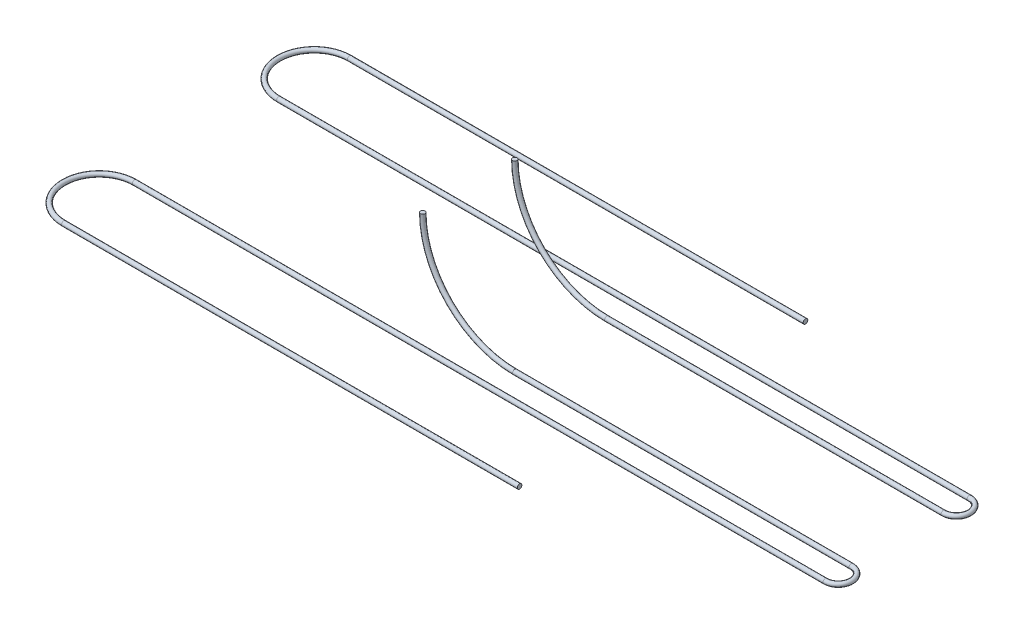
SolidWorks part; units mm, degrees
ref_plane "Front Plane" through (0, 0, 0) normal (0, 0, 1) x (1, 0, 0)
ref_plane "Top Plane" through (0, 0, 0) normal (0, 1, 0) x (1, 0, 0)
ref_plane "Right Plane" through (0, 0, 0) normal (1, 0, 0) x (0, 0, -1)
ref_plane "Plane1" through (0, 0, -10) normal (0, 0, 1) x (1, 0, 0)
sketch "Sketch1" plane through (0, 0, -10) normal (0, 0, 1) x (1, 0, 0)
  arc A1 (0, 0) -> (-20, 20) centre (0, 20) cw
  point P5 (0, 0)
  point P6 (0, 0)
  dimension "D1" = 20
sketch "Sketch3" plane through (0, 0, 0) normal (0, 1, 0) x (1, 0, 0)
  line L0 (0, 10) -> (73.09, 10)
  line L1 (-20, 10) -> (0, 10) construction
  line L2 (-14.7469, 10) -> (14.7469, 10) construction
  line L3 (73.09, 15.65) -> (-76.91, 15.65)
  line L4 (-76.91, 31.05) -> (22.09, 31.05)
  arc A0 (73.09, 10) -> (73.09, 15.65) centre (73.09, 12.825) ccw
  arc A1 (-76.91, 15.65) -> (-76.91, 31.05) centre (-76.91, 23.35) cw
  circle A2 centre (73.09, 13.5) radius 2.15 construction
  point P11 (0, 0)
  point P16 (80, 12.825)
  point P17 (80, 13.5)
  point P19 (0, 0)
  dimension "D1" = 13.5
  dimension "D2" = 7.7
  dimension "D6" = 4.3
  dimension "D3" = 73.09
  dimension "D4" = 150
  dimension "D5" = 99
ref_plane "Plane2" through (22.09, 0, 0) normal (1, 0, 0) x (0, 0, -1)
curve "CompCurve1"
sketch "Sketch4" plane through (22.09, 0, 0) normal (1, 0, 0) x (0, 0, -1)
  line L0 (31.05, 0) -> (15.65, 0) construction
  circle A0 centre (31.05, 0) radius 0.5
  point P4 (0, 0)
  point P5 (10.4055, 0)
  dimension "D1" = 1
sweep "Sweep1" add profiles "Sketch4" path "CompCurve1"
mirror "Mirror2" about plane through (0, 0, 0) normal (0, 0, 1) of bodies 103
